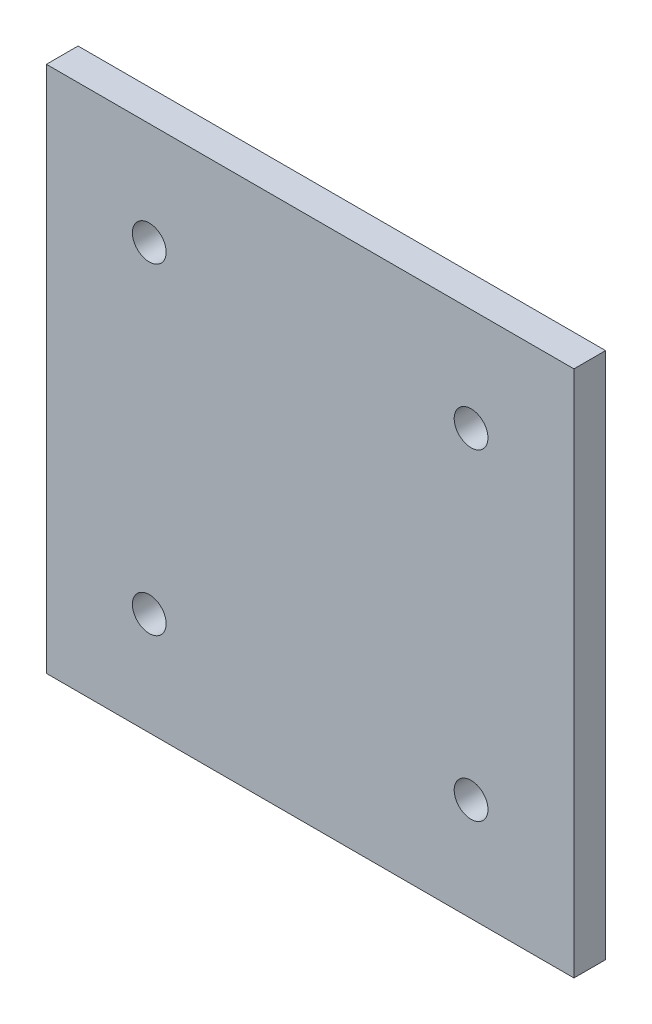
SolidWorks part; units mm, degrees
ref_plane "前视基准面" through (0, 0, 0) normal (0, 0, 1) x (1, 0, 0)
ref_plane "上视基准面" through (0, 0, 0) normal (0, 1, 0) x (1, 0, 0)
ref_plane "右视基准面" through (0, 0, 0) normal (1, 0, 0) x (0, 0, -1)
other "Configuration Table"
sketch "草图1" plane through (0, 0, 0) normal (0, 0, 1) x (1, 0, 0)
  line L0 (-25, -25) -> (25, -25)
  line L1 (25, -25) -> (25, 25)
  line L2 (25, 25) -> (-25, 25)
  line L3 (-25, 25) -> (-25, -25)
  circle A0 centre (-15.25, -15.25) radius 1.6
  circle A1 centre (-15.25, 15.25) radius 1.6
  circle A2 centre (15.25, -15.25) radius 1.6
  circle A3 centre (15.25, 15.25) radius 1.6
extrude "设备占位" add sketch "草图1" along normal blind 3
